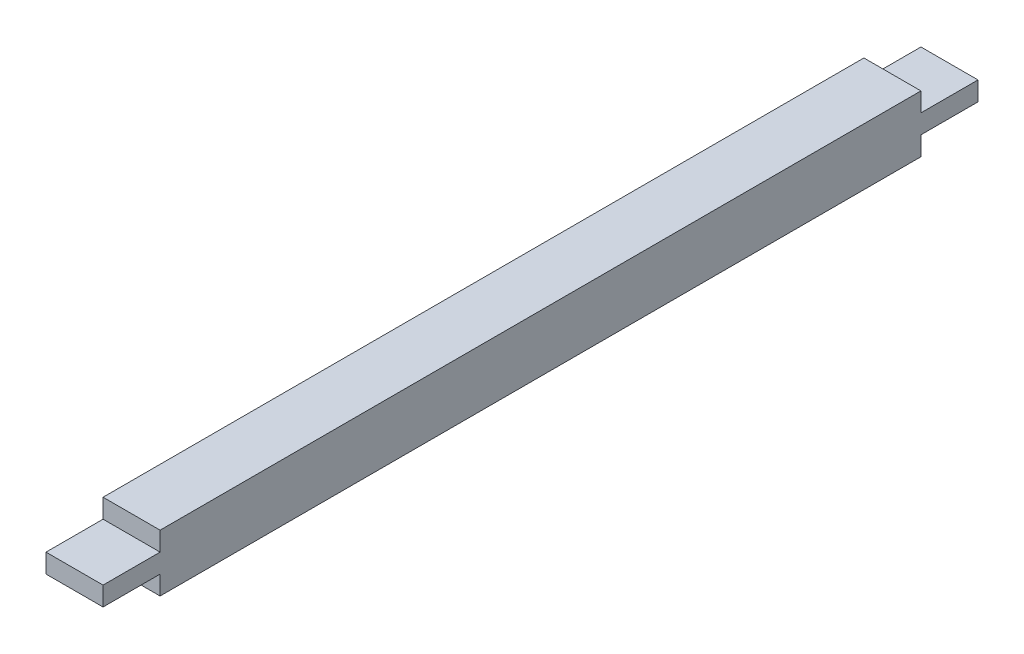
SolidWorks part; units mm, degrees
ref_plane "Alzado" through (0, 0, 0) normal (0, 0, 1) x (1, 0, 0)
ref_plane "Planta" through (0, 0, 0) normal (0, 1, 0) x (1, 0, 0)
ref_plane "Vista lateral" through (0, 0, 0) normal (1, 0, 0) x (0, 0, -1)
sketch "Croquis1" plane through (0, 0, 0) normal (0, 1, 0) x (1, 0, 0)
  line L0 (-165, 247.5995) -> (-165, -234.0755) construction
  line L1 (-150, -200) -> (150, -200) construction
  line L2 (-150, -200) -> (-150, 200) construction
  line L3 (-150, 200) -> (150, 200) construction
  line L4 (150, -200) -> (150, 200) construction
  line L5 (-150, -200) -> (150, 200) construction
  line L6 (-150, 200) -> (150, -200) construction
  line L7 (0, 0) -> (-198.4373, 0) construction
  line L9 (-179.997, -230) -> (-150.003, -230)
  line L10 (-179.997, -230) -> (-179.997, 230)
  line L11 (-179.997, 230) -> (-150.003, 230)
  line L12 (-150.003, -230) -> (-150.003, 230)
  line L13 (-179.997, -230) -> (-150.003, 230) construction
  line L14 (-179.997, 230) -> (-150.003, -230) construction
  point P0 (0, 0)
  point P10 (-165, 0)
  dimension "D1" = 300
  dimension "D2" = 400
  dimension "D3" = 15
  dimension "D4" = 30
  dimension "D5" = 30
extrude "Saliente-Extruir1" add sketch "Croquis1" along normal mid plane 10
sketch "Croquis2" plane through (0, 0, 0) normal (0, 1, 0) x (1, 0, 0)
  line L0 (-150.003, -230) -> (-150.003, 230) construction
  line L1 (-179.997, -200) -> (-150.003, -200)
  line L2 (-179.997, -200) -> (-179.997, 200)
  line L3 (-179.997, 200) -> (-150.003, 200)
  line L4 (-150.003, -200) -> (-150.003, 200)
  line L5 (-179.997, -200) -> (-150.003, 200) construction
  line L6 (-179.997, 200) -> (-150.003, -200) construction
  line L7 (-150.003, 230) -> (-179.997, 230) construction
  line L8 (-179.997, -230) -> (-150.003, -230) construction
  point P0 (-165, 0)
  point P9 (-165, -230)
  dimension "D1" = 30
  dimension "D2" = 30
extrude "Saliente-Extruir2" add sketch "Croquis2" along normal mid plane 30
